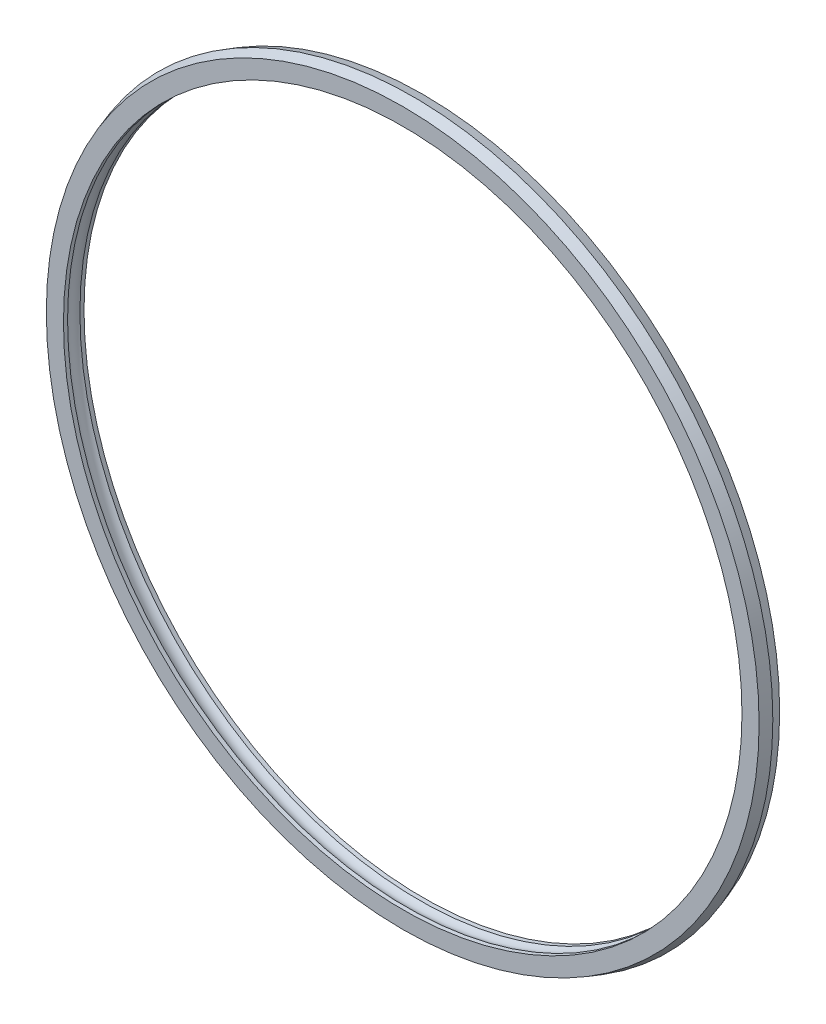
SolidWorks part; units mm, degrees
ref_plane "Front Plane" through (0, 0, 0) normal (0, 0, 1) x (1, 0, 0)
ref_plane "Top Plane" through (0, 0, 0) normal (0, 1, 0) x (1, 0, 0)
ref_plane "Right Plane" through (0, 0, 0) normal (1, 0, 0) x (0, 0, -1)
sketch "Sketch1" plane through (0, 0, 0) normal (1, 0, 0) x (0, 0, -1)
  line L0 (0, 0) -> (65.0135, 0) construction
  line L1 (0, 0) -> (0, 77.6931) construction
  line L2 (0, 52.5) -> (1.5, 52)
  line L3 (1.5, 52) -> (1.5, 49.5)
  line L4 (1.5, 49.5) -> (0.9, 49.5)
  line L5 (-1.5, 49.5) -> (-0.9, 49.5)
  line L6 (-1.5, 52) -> (-1.5, 49.5)
  line L7 (0, 52.5) -> (-1.5, 52)
  arc A0 (-0.9, 49.5) -> (0.9, 49.5) centre (0, 48.3) cw
  dimension "D2" = 3
  dimension "D3" = 1.5
  dimension "D1" = 3
  dimension "D4" = 1.8
  dimension "D5" = 2.5
  dimension "D6" = 99
revolve "Revolve1" add sketch "Sketch1" angle 360 about L0
